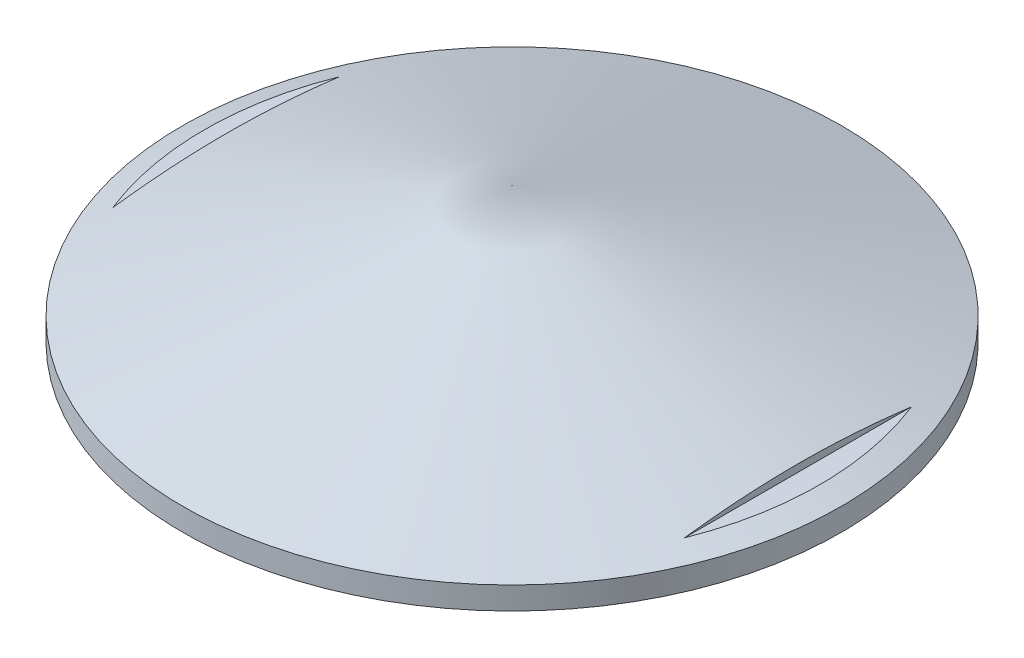
SolidWorks part; units mm, degrees
ref_plane "Front Plane" through (0, 0, 0) normal (0, 0, 1) x (1, 0, 0)
ref_plane "Top Plane" through (0, 0, 0) normal (0, 1, 0) x (1, 0, 0)
ref_plane "Right Plane" through (0, 0, 0) normal (1, 0, 0) x (0, 0, -1)
sketch "Sketch1" plane through (0, 0, 0) normal (0, 0, 1) x (1, 0, 0)
  line L0 (0, 76500) -> (0, 80000) construction
  line L1 (0, 80000) -> (4500, 80000)
  line L2 (4500, 80000) -> (4500, 76500)
  line L3 (4500, 76500) -> (4380, 76500)
  line L4 (4380, 76500) -> (4380, 80000)
  line L5 (4380, 80000) -> (0, 80000)
sketch "Sketch2" plane through (0, 0, 0) normal (0, 0, 1) x (1, 0, 0)
  line L0 (0, 76500) -> (0, 80000) construction
  line L1 (0, 78500) -> (4380, 77000)
  line L2 (4380, 76500) -> (4380, 80000) construction
  line L3 (4380, 77000) -> (4380, 76700)
  line L4 (4380, 76700) -> (0, 78200)
  line L5 (0, 78200) -> (0, 78500)
revolve "Revolve2" add sketch "Sketch2" angle 360 about L0
sketch "Sketch3" plane through (0, 0, 0) normal (0, 0, 1) x (1, 0, 0)
  line L0 (3800, 79400) -> (4500, 79400)
  line L1 (4500, 80000) -> (4500, 76500) construction
  line L2 (4500, 79400) -> (4500, 77100)
  line L3 (4500, 77100) -> (3800, 77100)
  line L4 (3800, 77100) -> (3800, 79400)
  line L5 (-3800, 79400) -> (-4600, 79400)
  line L6 (-4600, 79400) -> (-4600, 77100)
  line L7 (-4600, 77100) -> (-3800, 77100)
  line L8 (-3800, 77100) -> (-3800, 79400)
extrude "Cut-Extrude1" cut sketch "Sketch3" against normal mid plane 4000
